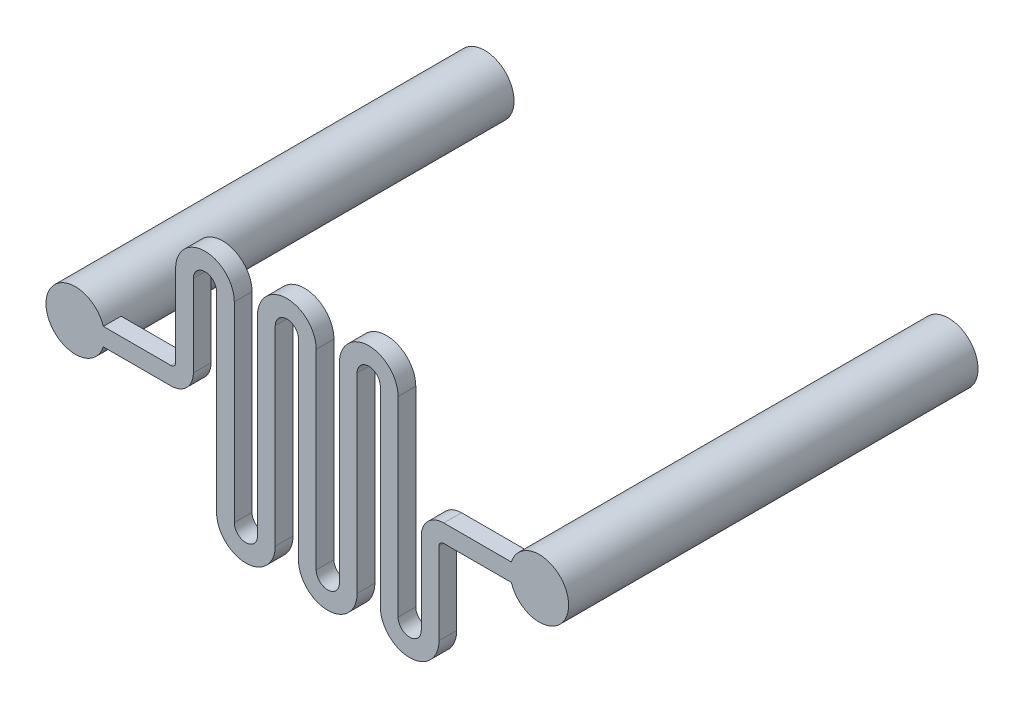
SolidWorks part; units mm, degrees
ref_plane "Front Plane" through (0, 0, 0) normal (0, 0, 1) x (1, 0, 0)
ref_plane "Top Plane" through (0, 0, 0) normal (0, 1, 0) x (1, 0, 0)
ref_plane "Right Plane" through (0, 0, 0) normal (1, 0, 0) x (0, 0, -1)
sketch "Sketch2" plane through (0, 0, 0) normal (0, 0, 1) x (1, 0, 0)
  line L3 (-20.5, -0.65) -> (-13.5, -0.65)
  line L6 (-11.85, 1) -> (-11.85, 7)
  line L9 (-10.15, 7) -> (-10.15, 0)
  line L12 (-10.15, 0) -> (-10.15, -7)
  line L15 (-5.85, -7) -> (-5.85, 0)
  line L18 (-5.85, 0) -> (-5.85, 7)
  line L21 (-4.15, 7) -> (-4.15, 0)
  line L22 (-4.15, 0) -> (-4.15, -7)
  line L23 (0.15, -7) -> (0.15, 0)
  line L24 (0.15, 0) -> (0.15, 7)
  line L25 (1.85, 7) -> (1.85, 0)
  line L26 (1.85, 0) -> (1.85, -7)
  line L27 (6.15, -7) -> (6.15, -1)
  line L28 (6.5, -0.65) -> (13.5, -0.65)
  line L29 (-20.5, 0.65) -> (-13.5, 0.65)
  line L30 (-13.15, 1) -> (-13.15, 7)
  line L31 (-8.85, 7) -> (-8.85, 0)
  line L32 (-8.85, 0) -> (-8.85, -7)
  line L33 (-7.15, -7) -> (-7.15, 0)
  line L34 (-7.15, 0) -> (-7.15, 7)
  line L35 (-2.85, 7) -> (-2.85, 0)
  line L36 (-2.85, 0) -> (-2.85, -7)
  line L37 (-1.15, -7) -> (-1.15, 0)
  line L38 (-1.15, 0) -> (-1.15, 7)
  line L39 (3.15, 7) -> (3.15, 0)
  line L40 (3.15, 0) -> (3.15, -7)
  line L41 (4.85, -7) -> (4.85, -1)
  line L42 (6.5, 0.65) -> (13.5, 0.65)
  arc A8 (-11.85, 1) -> (-13.5, -0.65) centre (-13.5, 1) cw
  arc A9 (-11.85, 7) -> (-10.15, 7) centre (-11, 7) cw
  arc A10 (-10.15, -7) -> (-5.85, -7) centre (-8, -7) ccw
  arc A11 (-5.85, 7) -> (-4.15, 7) centre (-5, 7) cw
  arc A12 (-4.15, -7) -> (0.15, -7) centre (-2, -7) ccw
  arc A13 (0.15, 7) -> (1.85, 7) centre (1, 7) cw
  arc A14 (1.85, -7) -> (6.15, -7) centre (4, -7) ccw
  arc A15 (6.15, -1) -> (6.5, -0.65) centre (6.5, -1) cw
  arc A16 (-13.15, 1) -> (-13.5, 0.65) centre (-13.5, 1) cw
  arc A17 (-13.15, 7) -> (-8.85, 7) centre (-11, 7) cw
  arc A18 (-8.85, -7) -> (-7.15, -7) centre (-8, -7) ccw
  arc A19 (-7.15, 7) -> (-2.85, 7) centre (-5, 7) cw
  arc A20 (-2.85, -7) -> (-1.15, -7) centre (-2, -7) ccw
  arc A21 (-1.15, 7) -> (3.15, 7) centre (1, 7) cw
  arc A22 (3.15, -7) -> (4.85, -7) centre (4, -7) ccw
  arc A23 (4.85, -1) -> (6.5, 0.65) centre (6.5, -1) cw
  arc A24 (-20.5, 0.65) -> (-20.5, -0.65) centre (-20.5, 0) ccw
  arc A25 (13.5, -0.65) -> (13.5, 0.65) centre (13.5, 0) ccw
  point P4 (0, 0)
  point P32 (5.5, 0)
  point P35 (-12.5, 0)
  dimension "D1" = 8
  dimension "D14" = 8
extrude "Boss-Extrude1" add sketch "Sketch2" along normal blind 1.3
ref_plane "Plane1" through (0, 0, 0) normal (0, 1, 0) x (1, 0, 0)
sketch "Sketch3" plane through (0, 0, 0) normal (0, 1, 0) x (1, 0, 0)
  line L1 (-20.5, 28.7) -> (-22.65, 28.7)
  line L2 (-20.5, -1.3) -> (-20.5, 28.7)
  line L6 (-22.65, 28.7) -> (-22.65, -1.3)
  line L7 (-22.65, -1.3) -> (-20.5, -1.3)
  dimension "D1" = 2.15
  dimension "D3" = 30
ref_plane "Plane2" through (0, 0, 0) normal (0, 1, 0) x (1, 0, 0)
sketch "Sketch4" plane through (0, 0, 0) normal (0, 1, 0) x (1, 0, 0)
  line L1 (13.5, 28.7) -> (15.65, 28.7)
  line L2 (13.5, -1.3) -> (13.5, 28.7)
  line L6 (15.65, 28.7) -> (15.65, -1.3)
  line L7 (15.65, -1.3) -> (13.5, -1.3)
  dimension "D1" = 2.15
  dimension "D3" = 30
revolve "Revolve1" add sketch "Sketch3" angle 360 about L2
revolve "Revolve2" add sketch "Sketch4" angle 360 about L2
sketch "Sketch5" plane through (0, 0, -28.7) normal (0, 0, -1) x (-1, 0, 0)
  circle A0 centre (-13.5, 0) radius 1.5
  circle A1 centre (20.5, 0) radius 1.5
  dimension "D1" = 3
  dimension "D2" = 3
extrude "Cut-Extrude1" cut sketch "Sketch5" against normal blind 28
